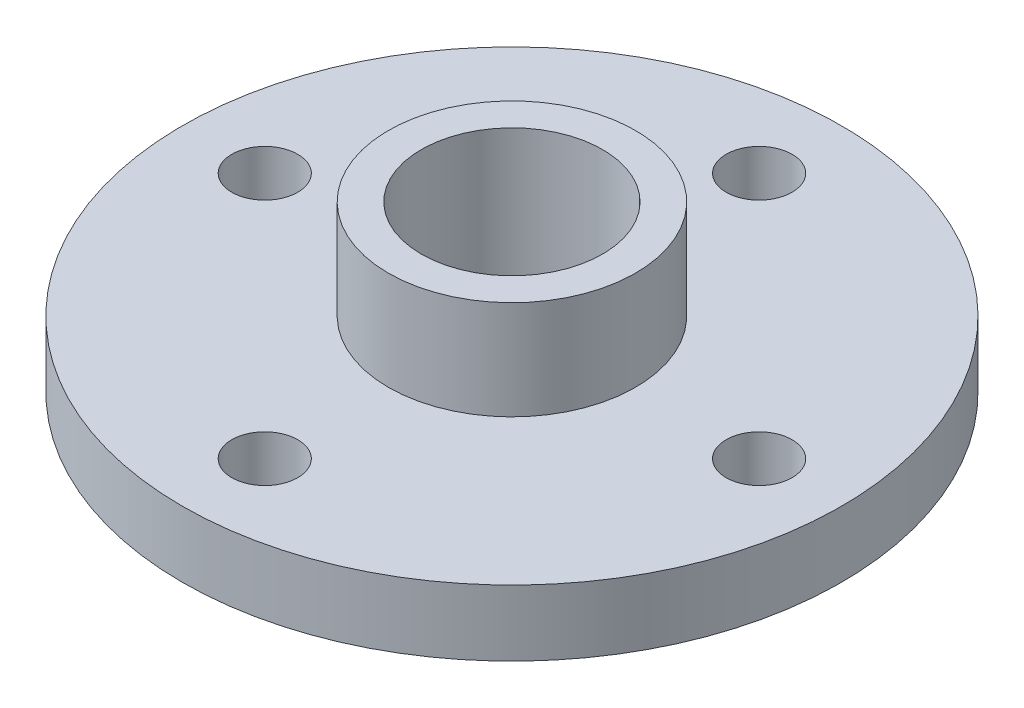
SolidWorks part; units mm, degrees
material "1060 Alloy"
ref_plane "Front Plane" through (0, 0, 0) normal (0, 0, 1) x (1, 0, 0)
ref_plane "Top Plane" through (0, 0, 0) normal (0, 1, 0) x (1, 0, 0)
ref_plane "Right Plane" through (0, 0, 0) normal (1, 0, 0) x (0, 0, -1)
sketch "Sketch2" plane through (0, 0, 0) normal (0, 1, 0) x (1, 0, 0)
  circle A0 centre (0, 0) radius 10
  dimension "D1" = 20
extrude "Boss-Extrude1" add sketch "Sketch2" along normal blind 2
sketch "Sketch3" plane through (0, 2, 0) normal (0, 1, 0) x (1, 0, 0)
  line L0 (0, 0) -> (0, 12.6294) construction
  line L1 (0, 0) -> (16.4383, 0) construction
  circle A1 centre (0, 7.5) radius 1
  circle A2 centre (7.5, 0) radius 1
  circle A3 centre (0, -7.5) radius 1
  circle A4 centre (-7.5, 0) radius 1
  dimension "D1" = 15
  dimension "D3" = 2
  dimension "D2" = 15
extrude "Cut-Extrude1" cut sketch "Sketch3" against normal through all
sketch "Sketch4" plane through (0, 2, 0) normal (0, 1, 0) x (1, 0, 0)
  circle A0 centre (0, 0) radius 3.75
  dimension "D1" = 7.5
extrude "Boss-Extrude2" add sketch "Sketch4" along normal blind 3
sketch "Sketch5" plane through (0, 5, 0) normal (0, 1, 0) x (1, 0, 0)
  circle A0 centre (0, 0) radius 1.5
  dimension "D1" = 3
extrude "Cut-Extrude2" cut sketch "Sketch5" against normal through all
sketch "Sketch6" plane through (0, 5, 0) normal (0, 1, 0) x (1, 0, 0)
  circle A0 centre (0, 0) radius 2.75
  dimension "D1" = 5.5
extrude "Cut-Extrude3" cut sketch "Sketch6" against normal blind 4.5
